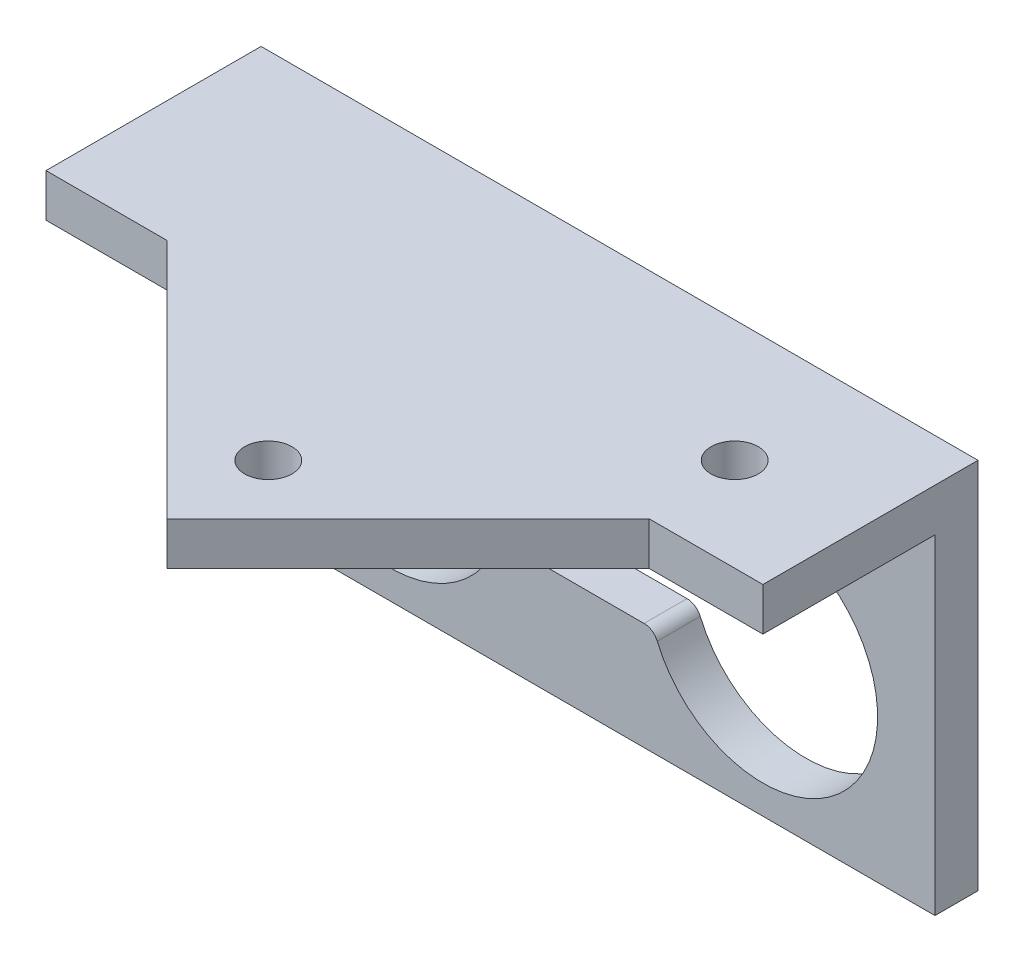
SolidWorks part; units mm, degrees
ref_plane "前视基准面" through (0, 0, 0) normal (0, 0, 1) x (1, 0, 0)
ref_plane "上视基准面" through (0, 0, 0) normal (0, 1, 0) x (1, 0, 0)
ref_plane "右视基准面" through (0, 0, 0) normal (1, 0, 0) x (0, 0, -1)
sketch "草图1" plane through (0, 0, 0) normal (0, 0, 1) x (1, 0, 0)
  line L1 (25, -10) -> (-25, -10)
  line L2 (25, -10) -> (25, 10)
  line L3 (25, 10) -> (-25, 10)
  line L4 (-25, -10) -> (-25, 10)
  line L5 (25, -10) -> (-25, 10) construction
  line L6 (25, 10) -> (-25, -10) construction
  line L8 (-4.7084, 2.5) -> (4.7084, 2.5)
  line L9 (4.7084, -2.5) -> (-4.7084, -2.5)
  line L10 (3.25, 7.25) -> (-3.25, 7.25) construction
  line L11 (3.25, 5.5) -> (-3.25, 5.5)
  line L12 (3.25, 9) -> (-3.25, 9)
  arc A7 (5.6297, -3.1111) -> (5.6297, 3.1111) centre (13, 0) ccw
  arc A8 (-5.6297, 3.1111) -> (-5.6297, -3.1111) centre (-13, 0) ccw
  arc A9 (4.7084, -2.5) -> (5.6297, -3.1111) centre (4.7084, -3.5) cw
  arc A10 (4.7084, 2.5) -> (5.6297, 3.1111) centre (4.7084, 3.5) ccw
  arc A11 (-4.7084, -2.5) -> (-5.6297, -3.1111) centre (-4.7084, -3.5) ccw
  arc A12 (-4.7084, 2.5) -> (-5.6297, 3.1111) centre (-4.7084, 3.5) cw
  arc A13 (3.25, 5.5) -> (3.25, 9) centre (3.25, 7.25) ccw
  arc A14 (-3.25, 9) -> (-3.25, 5.5) centre (-3.25, 7.25) ccw
  point P0 (0, 0)
  point P22 (0, 7.25)
  dimension "D3" = 1
  dimension "D4" = 8
  dimension "D5" = 8
  dimension "D6" = 2.5
  dimension "D8" = 13
  dimension "D9" = 13
  dimension "D12" = 1.75
  dimension "D1" = 20
  dimension "D2" = 50
  dimension "D7" = 2.5
  dimension "D10" = 7.25
  dimension "D11" = 6.5
  dimension "D13" = 3.25
extrude "凸台-拉伸1" add sketch "草图1" along normal blind 3
sketch "草图2" plane through (0, 10, 0) normal (0, 1, 0) x (1, 0, 0)
  line L1 (-25, 0) -> (25, 0)
  line L2 (-25, 0) -> (-25, -15)
  line L3 (-25, -15) -> (25, -15)
  line L4 (25, 0) -> (25, -15)
  dimension "D1" = 15
extrude "凸台-拉伸2" add sketch "草图2" along normal blind 6
sketch "草图5" plane through (0, 10, 0) normal (0, -1, 0) x (1, 0, 0)
  line L1 (25, 3) -> (-25, 3)
  line L2 (25, 3) -> (25, 15)
  line L3 (25, 15) -> (-25, 15)
  line L4 (-25, 3) -> (-25, 15)
extrude "切除-拉伸2" cut sketch "草图5" against normal blind 3
sketch "草图7" plane through (0, 16, 0) normal (0, 1, 0) x (1, 0, 0)
  line L6 (-16.5685, -15) -> (17.0711, -15)
  line L12 (0.2513, -31.8198) -> (-16.5685, -15)
  line L13 (0.2513, -31.8198) -> (17.0711, -15)
  circle A2 centre (0.2513, -24.7487) radius 1.65
extrude "凸台-拉伸3" add sketch "草图7" against normal blind 3
sketch "草图8" plane through (0, 16, 0) normal (0, 1, 0) x (1, 0, 0)
  circle A0 centre (16.5147, -8.4853) radius 1.65
  circle A2 centre (0.2513, -24.7487) radius 1.65 construction
  dimension "D1" = 23
  dimension "D2" = 3.3
extrude "切除-拉伸3" cut sketch "草图8" against normal blind 3
